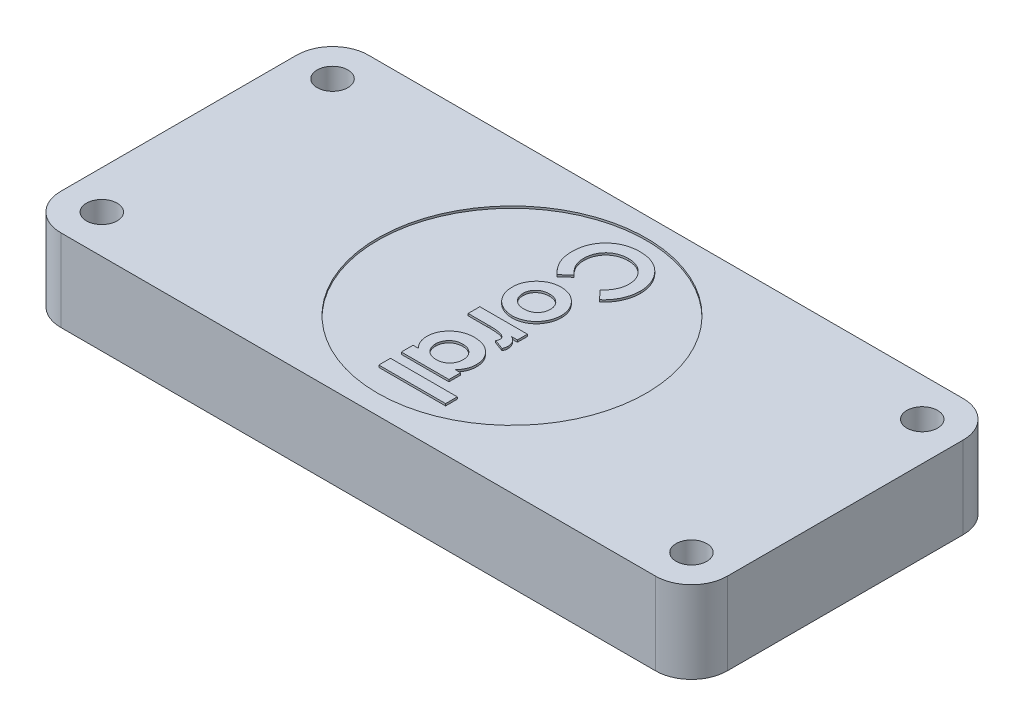
SolidWorks part; units mm, degrees
ref_plane "Front" through (0, 0, 0) normal (0, 0, 1) x (1, 0, 0)
ref_plane "Top" through (0, 0, 0) normal (0, 1, 0) x (1, 0, 0)
ref_plane "Right" through (0, 0, 0) normal (1, 0, 0) x (0, 0, -1)
sketch "Sketch1" plane through (0, 0, 0) normal (0, 1, 0) x (1, 0, 0)
  line L0 (0, 0) -> (0, 15) construction
  line L1 (-32.5, -15) -> (32.5, -15)
  line L2 (-32.5, -15) -> (-32.5, 15)
  line L3 (-32.5, 15) -> (32.5, 15)
  line L4 (32.5, -15) -> (32.5, 15)
  line L5 (-32.5, -15) -> (32.5, 15) construction
  line L6 (-32.5, 15) -> (32.5, -15) construction
  line L7 (0, 15) -> (0, 0) construction
  line L8 (0, 0) -> (-32.5, 0) construction
  circle A0 centre (-28.75, 11.25) radius 1.5
  circle A1 centre (-28.75, -11.25) radius 1.5
  circle A2 centre (28.75, 11.25) radius 1.5
  circle A3 centre (28.75, -11.25) radius 1.5
  point P0 (0, 0)
  dimension "D3" = 3
  dimension "D1" = 30
  dimension "D2" = 65
  dimension "D4" = 57.5
  dimension "D5" = 22.5
extrude "Boss-Extrude1" add sketch "Sketch1" along normal blind 8
fillet "Fillet1" radius 3.5 4 edges at (-32.5, 4, -15) (32.5, 4, -15) (32.5, 4, 15) (-32.5, 4, 15)
sketch "Sketch2" plane through (0, 8, 0) normal (0, 1, 0) x (1, 0, 0)
  line L0 (2.9244, 5.6173) -> (2.1256, 6.453)
  line L1 (-0.4236, 6.453) -> (-1.2746, 5.6427)
  line L2 (2.3164, -0.8141) -> (2.3164, -1.791)
  line L3 (2.3164, -1.791) -> (1.7452, -1.791)
  line L4 (2.2833, -3.2564) -> (1.3178, -2.9028)
  line L5 (-0.2188, -1.95) -> (-0.4452, -1.9538)
  line L6 (-0.4452, -1.9538) -> (-2.324, -1.9538)
  line L7 (-2.324, -1.9538) -> (-2.324, -0.8141)
  line L8 (-2.324, -0.8141) -> (2.3164, -0.8141)
  line L9 (2.3164, -7.3269) -> (2.3164, -8.4667)
  line L10 (2.3164, -8.4667) -> (-2.324, -8.4667)
  line L11 (-2.324, -8.4667) -> (-2.324, -7.3269)
  line L12 (-2.324, -7.3269) -> (-1.8177, -7.3269)
  line L13 (1.7936, -7.3269) -> (2.3164, -7.3269)
  line L14 (4.1888, -9.525) -> (4.1888, -10.6647)
  line L15 (4.1888, -10.6647) -> (-2.324, -10.6647)
  line L16 (-2.324, -10.6647) -> (-2.324, -9.525)
  line L17 (-2.324, -9.525) -> (4.1888, -9.525)
  circle A0 centre (0, 0) radius 13.1037
  spline S0 degree 3 poles (2.1256, 6.453) (2.2705, 6.589) (2.4743, 6.801) (2.6896, 7.1176) (2.8227, 7.354) (2.9232, 7.5992) (3.0218, 7.9346) (3.0494, 8.1965) (3.0491, 8.3713) knots 0 0 0 0 0.272304 0.399525 0.522811 0.642663 0.761023 1 1 1 1
  spline S1 degree 3 poles (3.0491, 8.3713) (3.048, 8.516) (3.0314, 8.731) (2.9635, 9.006) (2.8947, 9.201) (2.8054, 9.3869) (2.6961, 9.564) (2.5674, 9.732) (2.4203, 9.8886) (2.2595, 10.0319) (2.088, 10.1584) (1.9061, 10.2644) (1.7156, 10.3515) (1.5158, 10.4192) (1.2329, 10.4849) (1.0122, 10.5003) (0.8637, 10.5019) knots 0 0 0 0 0.127707 0.188882 0.249158 0.309661 0.370225 0.432332 0.495782 0.559304 0.621861 0.683322 0.744523 0.806088 0.868994 1 1 1 1
  spline S2 degree 3 poles (0.8637, 10.5019) (0.7592, 10.5024) (0.6041, 10.4945) (0.4015, 10.4656) (0.2564, 10.4349) (0.1159, 10.3964) (-0.0211, 10.3512) (-0.1527, 10.2946) (-0.2805, 10.2317) (-0.4009, 10.1586) (-0.5157, 10.0798) (-0.6244, 9.9943) (-0.7264, 9.9017) (-0.8203, 9.8005) (-0.9088, 9.6934) (-0.9897, 9.5786) (-1.0651, 9.4586) (-1.1306, 9.3321) (-1.1899, 9.2028) (-1.2381, 9.0685) (-1.2769, 8.9311) (-1.3099, 8.7908) (-1.3375, 8.5969) (-1.3489, 8.4492) (-1.3471, 8.3496) knots 0 0 0 0 0.090639 0.134485 0.177331 0.219265 0.260785 0.302317 0.343436 0.384181 0.424376 0.464181 0.504012 0.543822 0.583802 0.624419 0.665548 0.706675 0.747827 0.788895 0.830219 0.871707 0.913734 1 1 1 1
  spline S3 degree 3 poles (-1.3471, 8.3496) (-1.3465, 8.1829) (-1.3243, 7.9351) (-1.2399, 7.6195) (-1.1666, 7.433) (-1.0942, 7.2869) (-1.0273, 7.1757) (-0.9523, 7.0607) (-0.8666, 6.9438) (-0.7712, 6.8238) (-0.6245, 6.6578) (-0.507, 6.5342) (-0.4236, 6.453) knots 0 0 0 0 0.22997 0.340704 0.449355 0.505557 0.565303 0.628205 0.694729 0.765019 0.83958 1 1 1 1
  spline S4 degree 3 poles (-1.2746, 5.6427) (-1.3819, 5.7538) (-1.5392, 5.9173) (-1.7263, 6.1461) (-1.8527, 6.3093) (-1.965, 6.4709) (-2.0633, 6.631) (-2.15, 6.7876) (-2.2236, 6.9441) (-2.2861, 7.1014) (-2.34, 7.2632) (-2.3855, 7.4301) (-2.4223, 7.603) (-2.4517, 7.7804) (-2.4788, 8.028) (-2.4876, 8.2167) (-2.4868, 8.3446) knots 0 0 0 0 0.151816 0.22254 0.290278 0.354641 0.415798 0.474709 0.530426 0.58558 0.640906 0.697901 0.75542 0.814521 0.874462 1 1 1 1
  spline S5 degree 3 poles (-2.4868, 8.3446) (-2.4854, 8.5761) (-2.4608, 8.9187) (-2.3607, 9.3569) (-2.257, 9.6633) (-2.1244, 9.9534) (-1.9619, 10.2272) (-1.7698, 10.4841) (-1.5505, 10.7221) (-1.3083, 10.9374) (-1.0482, 11.1277) (-0.769, 11.2851) (-0.4748, 11.4158) (-0.1642, 11.518) (0.2801, 11.6161) (0.6266, 11.6421) (0.8612, 11.6417) knots 0 0 0 0 0.131837 0.194461 0.255346 0.315588 0.375627 0.436138 0.497779 0.55947 0.620278 0.680788 0.741492 0.803215 0.866493 1 1 1 1
  spline S6 degree 3 poles (0.8612, 11.6417) (1.016, 11.643) (1.2445, 11.6276) (1.5441, 11.5863) (1.7582, 11.5382) (1.9672, 11.4801) (2.1687, 11.4079) (2.3634, 11.3217) (2.5515, 11.2241) (2.7319, 11.1138) (2.903, 10.9906) (3.0661, 10.8576) (3.2191, 10.7117) (3.3632, 10.5549) (3.4978, 10.3867) (3.6246, 10.2079) (3.7406, 10.0181) (3.8455, 9.821) (3.938, 9.6191) (4.0153, 9.4128) (4.0795, 9.2031) (4.1273, 8.989) (4.1761, 8.698) (4.1872, 8.4754) (4.1888, 8.3267) knots 0 0 0 0 0.088512 0.130926 0.172904 0.214 0.254985 0.295291 0.335772 0.376181 0.416178 0.45635 0.496512 0.537041 0.578119 0.619725 0.662422 0.705299 0.74743 0.789433 0.831267 0.872825 0.91487 1 1 1 1
  spline S7 degree 3 poles (4.1888, 8.3267) (4.1889, 8.1993) (4.1786, 8.009) (4.145, 7.7572) (4.1073, 7.5711) (4.0626, 7.3859) (4.0039, 7.2039) (3.9386, 7.0224) (3.8605, 6.8442) (3.7752, 6.669) (3.6785, 6.5009) (3.5763, 6.3371) (3.4625, 6.1813) (3.3412, 6.0305) (3.1681, 5.836) (3.0237, 5.7028) (2.9244, 5.6173) knots 0 0 0 0 0.123904 0.185067 0.24684 0.308435 0.370241 0.432587 0.495925 0.559351 0.621943 0.684393 0.746986 0.809441 0.872508 1 1 1 1
  spline S8 degree 3 poles (2.3978, 2.4296) (2.3978, 2.3229) (2.3881, 2.1632) (2.3533, 1.9539) (2.3199, 1.7996) (2.2731, 1.6486) (2.217, 1.5002) (2.1526, 1.3529) (2.0759, 1.2105) (1.9927, 1.072) (1.9009, 0.9406) (1.8013, 0.8175) (1.6962, 0.7004) (1.5809, 0.5948) (1.461, 0.4938) (1.3323, 0.4031) (1.1979, 0.3191) (1.0585, 0.2442) (0.9151, 0.1793) (0.7698, 0.1229) (0.6207, 0.0788) (0.4697, 0.0423) (0.2627, 0.0111) (0.1055, -0.0006) (0, 0) knots 0 0 0 0 0.084364 0.126142 0.167706 0.209066 0.250973 0.293148 0.336041 0.378761 0.420893 0.462622 0.503914 0.545188 0.586138 0.627722 0.669585 0.711432 0.752691 0.793971 0.834592 0.875577 0.91664 1 1 1 1
  spline S9 degree 3 poles (0, 0) (-0.1062, 0.0001) (-0.2651, 0.0096) (-0.4732, 0.0445) (-0.6266, 0.078) (-0.7761, 0.1246) (-0.924, 0.1791) (-1.0683, 0.2459) (-1.2104, 0.3198) (-1.3463, 0.4044) (-1.4763, 0.4951) (-1.597, 0.5956) (-1.7122, 0.7004) (-1.818, 0.8144) (-1.9161, 0.9359) (-2.0076, 1.0638) (-2.0905, 1.1989) (-2.1634, 1.3397) (-2.2291, 1.4836) (-2.2838, 1.6316) (-2.3284, 1.7833) (-2.3629, 1.9389) (-2.3946, 2.1525) (-2.406, 2.3152) (-2.4054, 2.4245) knots 0 0 0 0 0.083839 0.125192 0.166335 0.207602 0.24867 0.290582 0.332926 0.374978 0.416741 0.457857 0.498809 0.539516 0.58042 0.62191 0.663502 0.705394 0.746864 0.788245 0.829736 0.871532 0.913825 1 1 1 1
  spline S10 degree 3 poles (-2.4054, 2.4245) (-2.4038, 2.5833) (-2.3859, 2.8198) (-2.3114, 3.1232) (-2.2347, 3.3393) (-2.1364, 3.5468) (-2.0148, 3.744) (-1.8722, 3.9327) (-1.7098, 4.1098) (-1.5317, 4.272) (-1.3416, 4.4137) (-1.1423, 4.534) (-0.9336, 4.6329) (-0.7152, 4.7091) (-0.408, 4.7838) (-0.1685, 4.8017) (-0.0076, 4.8032) knots 0 0 0 0 0.126884 0.188201 0.248894 0.309599 0.371125 0.433466 0.498143 0.562593 0.625474 0.687114 0.748125 0.809457 0.871431 1 1 1 1
  spline S11 degree 3 poles (-0.0076, 4.8032) (0.1642, 4.8029) (0.4188, 4.7797) (0.7449, 4.6972) (0.9747, 4.6102) (1.1935, 4.4988) (1.474, 4.3155) (1.6602, 4.1416) (1.7758, 4.0158) knots 0 0 0 0 0.256474 0.379237 0.500978 0.622367 0.744855 1 1 1 1
  spline S12 degree 3 poles (1.7758, 4.0158) (1.8776, 3.9052) (2.0118, 3.7266) (2.1573, 3.4712) (2.2462, 3.2757) (2.313, 3.0729) (2.3788, 2.7923) (2.3972, 2.5753) (2.3978, 2.4296) knots 0 0 0 0 0.258464 0.38258 0.504991 0.627227 0.749297 1 1 1 1
  spline S13 degree 3 poles (1.3395, 2.4041) (1.3371, 2.4907) (1.3309, 2.6202) (1.2878, 2.784) (1.2475, 2.9004) (1.1934, 3.0102) (1.1302, 3.1164) (1.0511, 3.2136) (0.9644, 3.3063) (0.868, 3.3905) (0.7631, 3.4622) (0.6535, 3.5263) (0.5353, 3.575) (0.4117, 3.6151) (0.2342, 3.6523) (0.0964, 3.665) (0.0025, 3.6635) knots 0 0 0 0 0.126803 0.187423 0.246518 0.306285 0.365703 0.426477 0.488622 0.550895 0.612679 0.673914 0.735734 0.798735 0.86329 1 1 1 1
  spline S14 degree 3 poles (0.0025, 3.6635) (-0.0936, 3.6638) (-0.2352, 3.6543) (-0.4167, 3.6162) (-0.5427, 3.5767) (-0.6622, 3.5269) (-0.7745, 3.4659) (-0.879, 3.3929) (-0.9756, 3.3101) (-1.0633, 3.2195) (-1.1386, 3.1202) (-1.2039, 3.0164) (-1.2564, 2.9057) (-1.297, 2.7896) (-1.3375, 2.6245) (-1.3454, 2.4951) (-1.3471, 2.408) knots 0 0 0 0 0.139456 0.204809 0.268587 0.330587 0.392213 0.45361 0.515092 0.576402 0.636039 0.695407 0.753981 0.813285 0.873377 1 1 1 1
  spline S15 degree 3 poles (-1.3471, 2.408) (-1.3468, 2.3206) (-1.3354, 2.1912) (-1.296, 2.0254) (-1.2551, 1.9084) (-1.2015, 1.7976) (-1.1358, 1.6926) (-1.0595, 1.5926) (-0.9702, 1.5008) (-0.8733, 1.4157) (-0.7682, 1.3412) (-0.6558, 1.2789) (-0.5369, 1.2278) (-0.4116, 1.1882) (-0.2321, 1.1507) (-0.0925, 1.1381) (0.0025, 1.1397) knots 0 0 0 0 0.126397 0.186939 0.246099 0.305348 0.364572 0.424924 0.486952 0.54955 0.611149 0.672922 0.73501 0.798049 0.862643 1 1 1 1
  spline S16 degree 3 poles (0.0025, 1.1397) (0.0974, 1.1394) (0.2373, 1.149) (0.4164, 1.1867) (0.5405, 1.2268) (0.6584, 1.2763) (0.7695, 1.3374) (0.8732, 1.4107) (0.969, 1.4939) (1.0555, 1.5859) (1.1326, 1.6834) (1.1963, 1.7888) (1.2489, 1.9001) (1.2893, 2.0174) (1.3301, 2.1846) (1.3376, 2.3158) (1.3395, 2.4041) knots 0 0 0 0 0.13784 0.202698 0.265406 0.326938 0.388125 0.449117 0.511101 0.572086 0.632197 0.691339 0.750564 0.810546 0.871335 1 1 1 1
  spline S17 degree 3 poles (1.7452, -1.791) (1.8452, -1.8426) (1.9878, -1.9304) (2.1405, -2.0859) (2.234, -2.2106) (2.3068, -2.3463) (2.3767, -2.5379) (2.3989, -2.6902) (2.3978, -2.7921) knots 0 0 0 0 0.268422 0.393205 0.51643 0.637793 0.758061 1 1 1 1
  spline S18 degree 3 poles (2.3978, -2.7921) (2.3961, -2.8681) (2.3787, -3.0293) (2.3177, -3.1796) (2.2833, -3.2564) knots 0 0 0 0 0.474168 1 1 1 1
  spline S19 degree 3 poles (1.3178, -2.9028) (1.3463, -2.8435) (1.3974, -2.7389) (1.4203, -2.6244) (1.4209, -2.5746) knots 0 0 0 0 0.570645 1 1 1 1
  spline S20 degree 3 poles (1.4209, -2.5746) (1.4208, -2.5321) (1.4114, -2.4669) (1.3745, -2.3878) (1.3393, -2.3292) (1.2903, -2.2761) (1.2335, -2.223) (1.1635, -2.1762) (1.0855, -2.1268) (0.99, -2.0848) (0.8761, -2.0487) (0.7423, -2.0166) (0.588, -1.9945) (0.4147, -1.9731) (0.1436, -1.9552) (-0.0699, -1.949) (-0.2188, -1.95) knots 0 0 0 0 0.066912 0.101141 0.136381 0.173598 0.214076 0.25798 0.305417 0.358685 0.420924 0.492691 0.574131 0.665182 0.766513 1 1 1 1
  spline S21 degree 3 poles (-1.8177, -7.3269) (-1.9151, -7.2191) (-2.0487, -7.0529) (-2.1891, -6.8149) (-2.2707, -6.6404) (-2.3308, -6.4618) (-2.39, -6.2134) (-2.4045, -6.0198) (-2.4054, -5.8895) knots 0 0 0 0 0.273944 0.399987 0.519719 0.636176 0.754371 1 1 1 1
  spline S22 degree 3 poles (-2.4054, -5.8895) (-2.407, -5.7426) (-2.3845, -5.5248) (-2.3123, -5.2446) (-2.2371, -5.044) (-2.1394, -4.8514) (-2.022, -4.6653) (-1.8808, -4.4888) (-1.7218, -4.3206) (-1.5469, -4.1665) (-1.3585, -4.0318) (-1.1593, -3.9183) (-0.95, -3.8253) (-0.7307, -3.7522) (-0.4194, -3.6813) (-0.1766, -3.664) (-0.0127, -3.6635) knots 0 0 0 0 0.121092 0.179634 0.238304 0.297437 0.357507 0.419513 0.4836 0.548295 0.611487 0.674313 0.737107 0.80016 0.864737 1 1 1 1
  spline S23 degree 3 poles (-0.0127, -3.6635) (0.156, -3.6648) (0.4061, -3.68) (0.7261, -3.7498) (0.9498, -3.8196) (1.1616, -3.9094) (1.3619, -4.0187) (1.55, -4.1491) (1.7228, -4.2994) (1.8813, -4.4617) (2.0192, -4.6353) (2.1363, -4.8175) (2.232, -5.0085) (2.3058, -5.2083) (2.3791, -5.4885) (2.3979, -5.7077) (2.3978, -5.8552) knots 0 0 0 0 0.139309 0.205474 0.269598 0.332253 0.39483 0.457376 0.520582 0.583374 0.644082 0.70304 0.761664 0.819844 0.878346 1 1 1 1
  spline S24 degree 3 poles (2.3978, -5.8552) (2.3994, -5.9922) (2.3791, -6.1954) (2.3158, -6.458) (2.2493, -6.6462) (2.1652, -6.8286) (2.023, -7.064) (1.8919, -7.2267) (1.7936, -7.3269) knots 0 0 0 0 0.251537 0.373434 0.495667 0.61768 0.742091 1 1 1 1
  spline S25 degree 3 poles (1.3395, -6.0943) (1.3381, -6.0054) (1.3293, -5.8733) (1.2899, -5.7039) (1.2472, -5.5855) (1.1951, -5.472) (1.1299, -5.3652) (1.0527, -5.2641) (0.9656, -5.1694) (0.8698, -5.083) (0.7653, -5.0086) (0.6549, -4.9454) (0.5383, -4.8919) (0.414, -4.8536) (0.2373, -4.8124) (0.0985, -4.8052) (0.0051, -4.8032) knots 0 0 0 0 0.128421 0.189996 0.250359 0.309744 0.369856 0.430537 0.492876 0.555257 0.616197 0.677577 0.738631 0.800922 0.864882 1 1 1 1
  spline S26 degree 3 poles (0.0051, -4.8032) (-0.0893, -4.8049) (-0.229, -4.813) (-0.4081, -4.8527) (-0.5329, -4.8954) (-0.652, -4.9475) (-0.7649, -5.0109) (-0.8694, -5.0888) (-0.9682, -5.1752) (-1.0564, -5.2718) (-1.1348, -5.3735) (-1.2003, -5.4815) (-1.2532, -5.5947) (-1.2964, -5.7128) (-1.3352, -5.8806) (-1.3467, -6.0112) (-1.3471, -6.0994) knots 0 0 0 0 0.135365 0.199461 0.262264 0.323991 0.385461 0.447171 0.510418 0.573171 0.634271 0.693954 0.753723 0.813084 0.873629 1 1 1 1
  spline S27 degree 3 poles (-1.3471, -6.0994) (-1.3456, -6.19) (-1.3371, -6.3242) (-1.2976, -6.4962) (-1.2546, -6.6162) (-1.2029, -6.7312) (-1.1389, -6.8403) (-1.062, -6.9422) (-0.9741, -7.0375) (-0.8775, -7.1247) (-0.7716, -7.2002) (-0.6598, -7.2659) (-0.5394, -7.3176) (-0.4126, -7.3586) (-0.2303, -7.3988) (-0.0875, -7.4066) (0.0089, -7.4083) knots 0 0 0 0 0.128662 0.18979 0.249707 0.309189 0.3685 0.428644 0.489937 0.552121 0.612878 0.67405 0.735729 0.798305 0.862953 1 1 1 1
  spline S28 degree 3 poles (0.0089, -7.4083) (0.1032, -7.4067) (0.2431, -7.3988) (0.4218, -7.3584) (0.5465, -7.3182) (0.664, -7.2656) (0.7731, -7.1998) (0.8775, -7.1252) (0.9715, -7.0369) (1.0588, -6.9422) (1.1334, -6.8388) (1.1977, -6.73) (1.2505, -6.6151) (1.2892, -6.4931) (1.33, -6.3205) (1.3378, -6.1852) (1.3395, -6.0943) knots 0 0 0 0 0.135096 0.199063 0.261548 0.322044 0.382646 0.443385 0.505155 0.566516 0.627254 0.687026 0.74697 0.807539 0.869733 1 1 1 1
extrude "Cut-Extrude1" cut sketch "Sketch2" against normal blind 0.2 contours A0 L16 L17 L14 L15 S6 S7 L0 S0 S1 S2 S3 L1 S4 S5 S11 S12 S8 S9 S10 S19 S20 L5 L6 L7 L8 L2 L3 S17 S18 L4 S23 S24 L13 L9 L10 L11 L12 S21 S22 | S15 S16 S13 S14 | S27 S28 S25 S26
